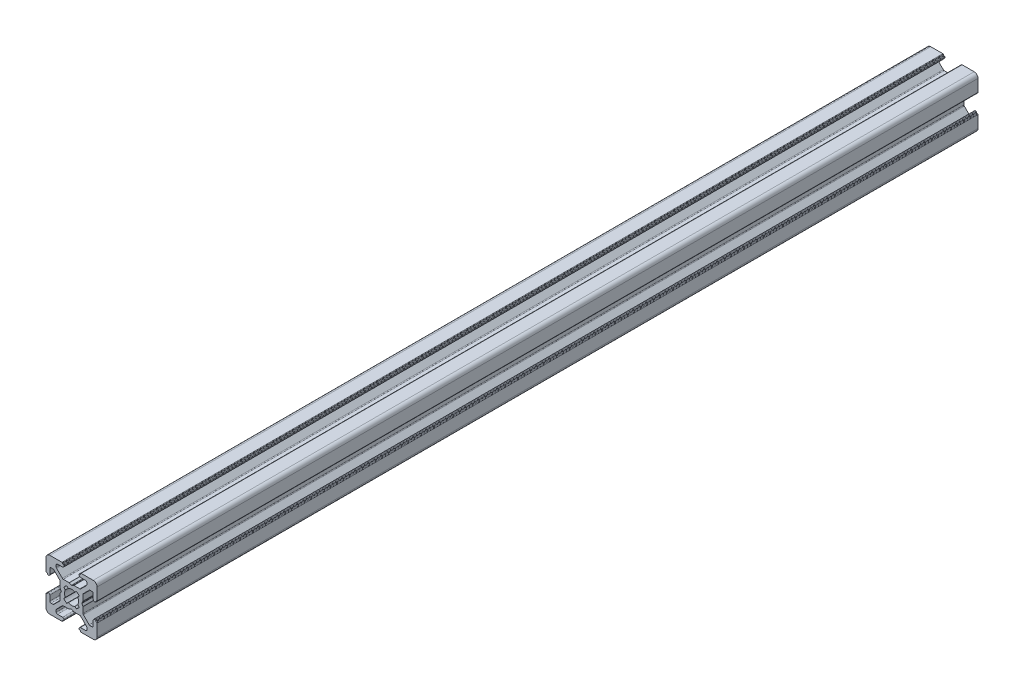
SolidWorks part; units mm, degrees
ref_plane "Front Plane" through (0, 0, 0) normal (0, 0, 1) x (1, 0, 0)
ref_plane "Top Plane" through (0, 0, 0) normal (0, 1, 0) x (1, 0, 0)
ref_plane "Right Plane" through (0, 0, 0) normal (1, 0, 0) x (0, 0, -1)
sketch "Sketch1" plane through (0, 0, 0) normal (0, 0, 1) x (1, 0, 0)
  line L0 (0, 13.3675) -> (0, -10.9159) construction
  line L1 (-12.9725, 0) -> (15.1887, 0) construction
  line L2 (-3.5, 8.5) -> (-5.5, 8.5)
  line L3 (-3.55, 9.7) -> (-3.55, 9.8)
  line L4 (-6, 7.2678) -> (-6, 8)
  line L5 (-7.2678, 6) -> (-8, 6)
  line L6 (-3.75, 10) -> (-8.5, 10)
  line L7 (-9.7, 3.55) -> (-9.8, 3.55)
  line L8 (-9.5, 3.2) -> (-9.5, 3.35)
  line L9 (-9, 3) -> (-9.3, 3)
  line L10 (-4.4732, 0.8536) -> (-4.0381, 0.1)
  line L11 (-4.5, 3.2322) -> (-4.5, 0.9536)
  line L12 (-8.5, 3.5) -> (-8.5, 5.5)
  line L13 (-10, 3.75) -> (-10, 8.5)
  line L14 (-3.5858, 4.6464) -> (-5.8536, 6.9142)
  line L15 (-4.6464, 3.5858) -> (-6.9142, 5.8536)
  line L16 (-3.2, 9.5) -> (-3.35, 9.5)
  line L17 (-3, 9) -> (-3, 9.3)
  line L18 (-0.8536, 4.4732) -> (-0.1, 4.0381)
  line L19 (-3.2322, 4.5) -> (-0.9536, 4.5)
  line L20 (-1.2582, 2.4453) -> (-1.9139, 2.9896)
  line L21 (-2.4453, 1.2582) -> (-2.9922, 1.9099)
  line L22 (3.5, -8.5) -> (5.5, -8.5)
  line L23 (3.55, -9.7) -> (3.55, -9.8)
  line L24 (6, -7.2678) -> (6, -8)
  line L25 (7.2678, -6) -> (8, -6)
  line L26 (3.75, -10) -> (8.5, -10)
  line L27 (9.7, -3.55) -> (9.8, -3.55)
  line L28 (9.5, -3.2) -> (9.5, -3.35)
  line L29 (9, -3) -> (9.3, -3)
  line L30 (4.4732, -0.8536) -> (4.0381, -0.1)
  line L31 (4.5, -3.2322) -> (4.5, -0.9536)
  line L32 (8.5, -3.5) -> (8.5, -5.5)
  line L33 (10, -3.75) -> (10, -8.5)
  line L34 (3.5858, -4.6464) -> (5.8536, -6.9142)
  line L35 (4.6464, -3.5858) -> (6.9142, -5.8536)
  line L36 (3.2, -9.5) -> (3.35, -9.5)
  line L37 (3, -9) -> (3, -9.3)
  line L38 (0.8536, -4.4732) -> (0.1, -4.0381)
  line L39 (3.2322, -4.5) -> (0.9536, -4.5)
  line L40 (1.2582, -2.4453) -> (1.9139, -2.9896)
  line L41 (2.4453, -1.2582) -> (2.9922, -1.9099)
  line L42 (-2.4453, -1.2582) -> (-2.9922, -1.9099)
  line L43 (-1.2582, -2.4453) -> (-1.9139, -2.9896)
  line L44 (-3.2322, -4.5) -> (-0.9536, -4.5)
  line L45 (-0.8536, -4.4732) -> (-0.1, -4.0381)
  line L46 (-3, -9) -> (-3, -9.3)
  line L47 (-3.2, -9.5) -> (-3.35, -9.5)
  line L48 (-4.6464, -3.5858) -> (-6.9142, -5.8536)
  line L49 (-3.5858, -4.6464) -> (-5.8536, -6.9142)
  line L50 (-10, -3.75) -> (-10, -8.5)
  line L51 (-8.5, -3.5) -> (-8.5, -5.5)
  line L52 (-4.5, -3.2322) -> (-4.5, -0.9536)
  line L53 (-4.4732, -0.8536) -> (-4.0381, -0.1)
  line L54 (-9, -3) -> (-9.3, -3)
  line L55 (-9.5, -3.2) -> (-9.5, -3.35)
  line L56 (-9.7, -3.55) -> (-9.8, -3.55)
  line L57 (2.4453, 1.2582) -> (2.9922, 1.9099)
  line L58 (1.2582, 2.4453) -> (1.9139, 2.9896)
  line L59 (3.2322, 4.5) -> (0.9536, 4.5)
  line L60 (0.8536, 4.4732) -> (0.1, 4.0381)
  line L61 (-3.75, -10) -> (-8.5, -10)
  line L62 (-7.2678, -6) -> (-8, -6)
  line L63 (-6, -7.2678) -> (-6, -8)
  line L64 (3, 9) -> (3, 9.3)
  line L65 (3.2, 9.5) -> (3.35, 9.5)
  line L66 (4.6464, 3.5858) -> (6.9142, 5.8536)
  line L67 (3.5858, 4.6464) -> (5.8536, 6.9142)
  line L68 (10, 3.75) -> (10, 8.5)
  line L69 (8.5, 3.5) -> (8.5, 5.5)
  line L70 (4.5, 3.2322) -> (4.5, 0.9536)
  line L71 (4.4732, 0.8536) -> (4.0381, 0.1)
  line L72 (9, 3) -> (9.3, 3)
  line L73 (9.5, 3.2) -> (9.5, 3.35)
  line L74 (9.7, 3.55) -> (9.8, 3.55)
  line L75 (3.75, 10) -> (8.5, 10)
  line L76 (7.2678, 6) -> (8, 6)
  line L77 (6, 7.2678) -> (6, 8)
  line L78 (3.55, 9.7) -> (3.55, 9.8)
  line L79 (3.5, 8.5) -> (5.5, 8.5)
  line L80 (-3.55, -9.7) -> (-3.55, -9.8)
  line L81 (-3.5, -8.5) -> (-5.5, -8.5)
  arc A0 (-10, 8.5) -> (-8.5, 10) centre (-8.5, 8.5) cw
  arc A1 (-8.5, 5.5) -> (-8, 6) centre (-8, 5.5) cw
  arc A2 (-7.2678, 6) -> (-6.9142, 5.8536) centre (-7.2678, 5.5) cw
  arc A3 (-5.8536, 6.9142) -> (-6, 7.2678) centre (-5.5, 7.2678) cw
  arc A4 (-6, 8) -> (-5.5, 8.5) centre (-5.5, 8) cw
  arc A5 (-9.7, 3.55) -> (-9.5, 3.35) centre (-9.7, 3.35) cw
  arc A6 (-9.8, 3.55) -> (-10, 3.75) centre (-9.8, 3.75) cw
  arc A7 (-9.3, 3) -> (-9.5, 3.2) centre (-9.3, 3.2) cw
  arc A8 (-8.5, 3.5) -> (-9, 3) centre (-9, 3.5) cw
  arc A9 (-4.6464, 3.5858) -> (-4.5, 3.2322) centre (-5, 3.2322) cw
  arc A10 (-4.4732, 0.8536) -> (-4.5, 0.9536) centre (-4.3, 0.9536) cw
  arc A11 (-4.0381, 0.1) -> (-4.0381, -0.1) centre (-4.2113, 0) cw
  arc A12 (-3.2, 9.5) -> (-3, 9.3) centre (-3.2, 9.3) cw
  arc A13 (-0.9536, 4.5) -> (-0.8536, 4.4732) centre (-0.9536, 4.3) cw
  arc A14 (-2.9922, 1.9099) -> (-1.9139, 2.9896) centre (0, 0) cw
  arc A15 (-3.2322, 4.5) -> (-3.5858, 4.6464) centre (-3.2322, 5) cw
  arc A16 (-3.75, 10) -> (-3.55, 9.8) centre (-3.75, 9.8) cw
  arc A17 (-3.35, 9.5) -> (-3.55, 9.7) centre (-3.35, 9.7) cw
  arc A18 (2.4453, -1.2582) -> (2.4453, 1.2582) centre (0, 0) ccw
  arc A19 (-3, 9) -> (-3.5, 8.5) centre (-3.5, 9) cw
  arc A20 (-2.4453, -1.2582) -> (-2.4453, 1.2582) centre (0, 0) cw
  arc A21 (10, -8.5) -> (8.5, -10) centre (8.5, -8.5) cw
  arc A22 (8.5, -5.5) -> (8, -6) centre (8, -5.5) cw
  arc A23 (7.2678, -6) -> (6.9142, -5.8536) centre (7.2678, -5.5) cw
  arc A24 (5.8536, -6.9142) -> (6, -7.2678) centre (5.5, -7.2678) cw
  arc A25 (6, -8) -> (5.5, -8.5) centre (5.5, -8) cw
  arc A26 (9.7, -3.55) -> (9.5, -3.35) centre (9.7, -3.35) cw
  arc A27 (9.8, -3.55) -> (10, -3.75) centre (9.8, -3.75) cw
  arc A28 (9.3, -3) -> (9.5, -3.2) centre (9.3, -3.2) cw
  arc A29 (8.5, -3.5) -> (9, -3) centre (9, -3.5) cw
  arc A30 (4.6464, -3.5858) -> (4.5, -3.2322) centre (5, -3.2322) cw
  arc A31 (4.4732, -0.8536) -> (4.5, -0.9536) centre (4.3, -0.9536) cw
  arc A32 (3.2, -9.5) -> (3, -9.3) centre (3.2, -9.3) cw
  arc A33 (-0.1, -4.0381) -> (0.1, -4.0381) centre (0, -4.2113) cw
  arc A34 (0.9536, -4.5) -> (0.8536, -4.4732) centre (0.9536, -4.3) cw
  arc A35 (2.9922, -1.9099) -> (1.9139, -2.9896) centre (0, 0) cw
  arc A36 (1.2582, -2.4453) -> (-1.2582, -2.4453) centre (0, 0) cw
  arc A37 (3.2322, -4.5) -> (3.5858, -4.6464) centre (3.2322, -5) cw
  arc A38 (3.75, -10) -> (3.55, -9.8) centre (3.75, -9.8) cw
  arc A39 (3.35, -9.5) -> (3.55, -9.7) centre (3.35, -9.7) cw
  arc A40 (3, -9) -> (3.5, -8.5) centre (3.5, -9) cw
  arc A41 (-3, -9) -> (-3.5, -8.5) centre (-3.5, -9) ccw
  arc A42 (-3.35, -9.5) -> (-3.55, -9.7) centre (-3.35, -9.7) ccw
  arc A43 (-3.75, -10) -> (-3.55, -9.8) centre (-3.75, -9.8) ccw
  arc A44 (-3.2322, -4.5) -> (-3.5858, -4.6464) centre (-3.2322, -5) ccw
  arc A45 (-2.9922, -1.9099) -> (-1.9139, -2.9896) centre (0, 0) ccw
  arc A46 (-0.9536, -4.5) -> (-0.8536, -4.4732) centre (-0.9536, -4.3) ccw
  arc A47 (-3.2, -9.5) -> (-3, -9.3) centre (-3.2, -9.3) ccw
  arc A48 (-4.4732, -0.8536) -> (-4.5, -0.9536) centre (-4.3, -0.9536) ccw
  arc A49 (3, 9) -> (3.5, 8.5) centre (3.5, 9) ccw
  arc A50 (3.35, 9.5) -> (3.55, 9.7) centre (3.35, 9.7) ccw
  arc A51 (3.75, 10) -> (3.55, 9.8) centre (3.75, 9.8) ccw
  arc A52 (3.2322, 4.5) -> (3.5858, 4.6464) centre (3.2322, 5) ccw
  arc A53 (1.2582, 2.4453) -> (-1.2582, 2.4453) centre (0, 0) ccw
  arc A54 (-4.6464, -3.5858) -> (-4.5, -3.2322) centre (-5, -3.2322) ccw
  arc A55 (-8.5, -3.5) -> (-9, -3) centre (-9, -3.5) ccw
  arc A56 (-9.3, -3) -> (-9.5, -3.2) centre (-9.3, -3.2) ccw
  arc A57 (-9.8, -3.55) -> (-10, -3.75) centre (-9.8, -3.75) ccw
  arc A58 (-9.7, -3.55) -> (-9.5, -3.35) centre (-9.7, -3.35) ccw
  arc A59 (-6, -8) -> (-5.5, -8.5) centre (-5.5, -8) ccw
  arc A60 (2.9922, 1.9099) -> (1.9139, 2.9896) centre (0, 0) ccw
  arc A61 (0.9536, 4.5) -> (0.8536, 4.4732) centre (0.9536, 4.3) ccw
  arc A62 (-0.1, 4.0381) -> (0.1, 4.0381) centre (0, 4.2113) ccw
  arc A63 (-5.8536, -6.9142) -> (-6, -7.2678) centre (-5.5, -7.2678) ccw
  arc A64 (-7.2678, -6) -> (-6.9142, -5.8536) centre (-7.2678, -5.5) ccw
  arc A65 (-8.5, -5.5) -> (-8, -6) centre (-8, -5.5) ccw
  arc A66 (-10, -8.5) -> (-8.5, -10) centre (-8.5, -8.5) ccw
  arc A67 (3.2, 9.5) -> (3, 9.3) centre (3.2, 9.3) ccw
  arc A68 (4.0381, 0.1) -> (4.0381, -0.1) centre (4.2113, 0) ccw
  arc A69 (4.4732, 0.8536) -> (4.5, 0.9536) centre (4.3, 0.9536) ccw
  arc A70 (4.6464, 3.5858) -> (4.5, 3.2322) centre (5, 3.2322) ccw
  arc A71 (8.5, 3.5) -> (9, 3) centre (9, 3.5) ccw
  arc A72 (9.3, 3) -> (9.5, 3.2) centre (9.3, 3.2) ccw
  arc A73 (9.8, 3.55) -> (10, 3.75) centre (9.8, 3.75) ccw
  arc A74 (9.7, 3.55) -> (9.5, 3.35) centre (9.7, 3.35) ccw
  arc A75 (6, 8) -> (5.5, 8.5) centre (5.5, 8) ccw
  arc A76 (5.8536, 6.9142) -> (6, 7.2678) centre (5.5, 7.2678) ccw
  arc A77 (7.2678, 6) -> (6.9142, 5.8536) centre (7.2678, 5.5) ccw
  arc A78 (8.5, 5.5) -> (8, 6) centre (8, 5.5) ccw
  arc A79 (10, 8.5) -> (8.5, 10) centre (8.5, 8.5) ccw
  dimension "D4" = 5.5
  dimension "D1" = 6
  dimension "D2" = 20
  dimension "D3" = 20
  dimension "D5" = 5.5
  dimension "D6" = 10
  dimension "D7" = 6
  dimension "D8" = 6
  dimension "D9" = 6
extrude "Extrude1" add sketch "Sketch1" along normal blind 345
